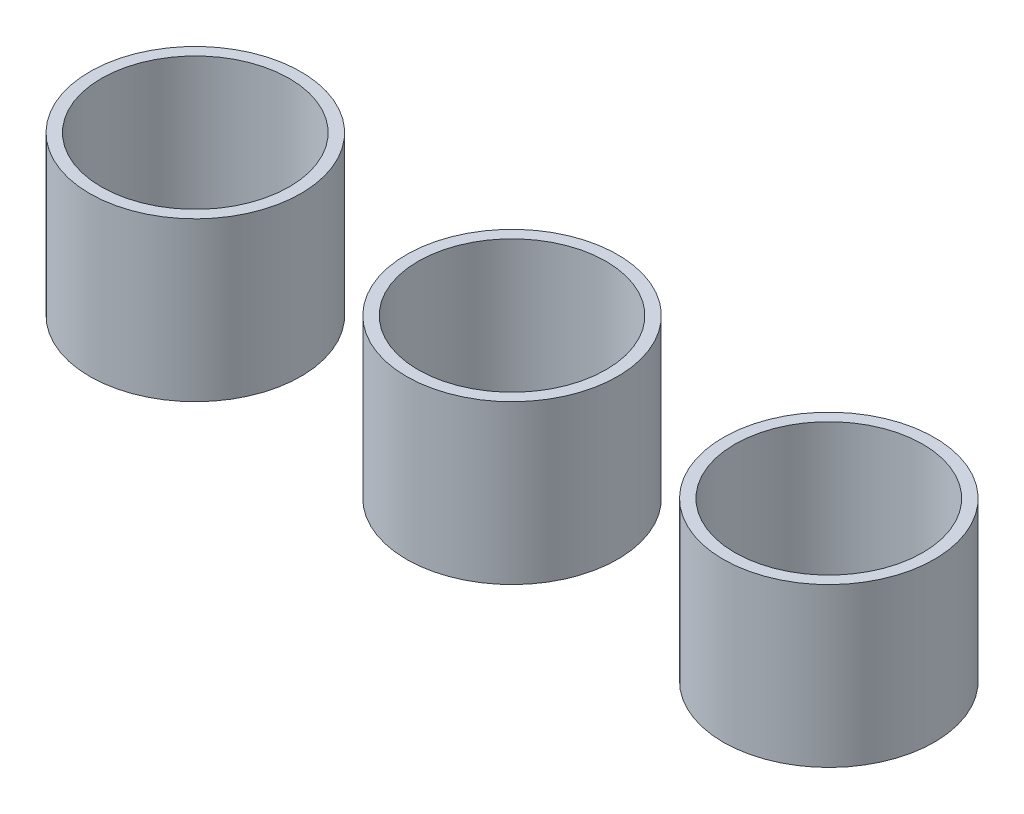
SolidWorks part; units mm, degrees
ref_plane "前视基准面" through (0, 0, 0) normal (0, 0, 1) x (1, 0, 0)
ref_plane "上视基准面" through (0, 0, 0) normal (0, 1, 0) x (1, 0, 0)
ref_plane "右视基准面" through (0, 0, 0) normal (1, 0, 0) x (0, 0, -1)
other "Configuration Table"
sketch "草图1" plane through (0, 0, 0) normal (0, 1, 0) x (1, 0, 0)
  circle A0 centre (0, 0) radius 10
  circle A1 centre (30, 0) radius 10
  circle A2 centre (60, 0) radius 10
  dimension "D1" = 20
extrude "拉伸-薄壁1" add sketch "草图1" along normal blind 15 thin thin type one direction reverse wall 1.1
